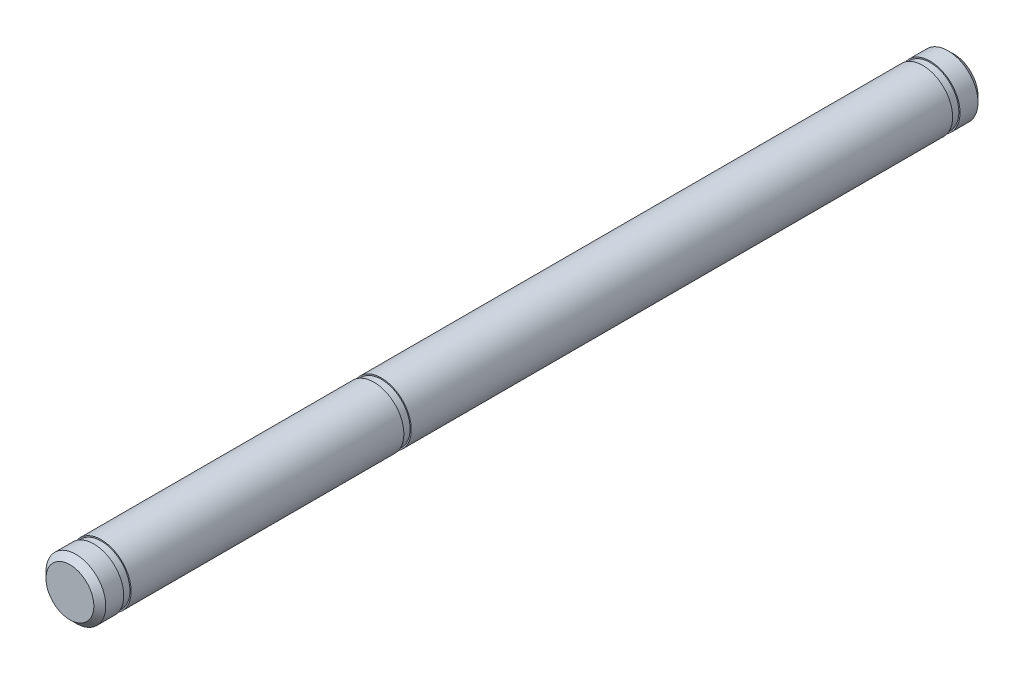
SolidWorks part; units mm, degrees
ref_plane "Front Plane" through (0, 0, 0) normal (0, 0, 1) x (1, 0, 0)
ref_plane "Top Plane" through (0, 0, 0) normal (0, 1, 0) x (1, 0, 0)
ref_plane "Right Plane" through (0, 0, 0) normal (1, 0, 0) x (0, 0, -1)
sketch "Sketch1" plane through (0, 0, 0) normal (0, 0, 1) x (1, 0, 0)
  line L0 (-2.5, 0) -> (2.5, 0) construction
  line L5 (0, 2.5) -> (0, -2.5) construction
  circle A1 centre (0, 0) radius 2.5
  point P7 (-2.5, 0)
  point P8 (2.5, 0)
  point P12 (0, -2.5)
  point P13 (0, 2.5)
  dimension "Diameter" = 5
sketch "Sketch2" plane through (0, 0, 0) normal (1, 0, 0) x (0, 0, -1)
  line L0 (-45, -2.5) -> (-45, 2.5) construction
  line L1 (50, -2.5) -> (-50, -2.5)
  line L2 (50, -2.5) -> (50, 2.5)
  line L3 (50, 2.5) -> (-50, 2.5)
  line L4 (-50, -2.5) -> (-50, 2.5)
  line L5 (50, -2.5) -> (-50, 2.5) construction
  line L6 (50, 2.5) -> (-50, -2.5) construction
  line L7 (45, -2.5) -> (45, 2.5) construction
  line L8 (-50, 2.15) -> (-49.65, 2.5) construction
  point P0 (0, 0)
  point P8 (-50, 2.5)
  point P9 (50, 2.5)
  point P14 (-45, 2.5)
  point P15 (-45, -2.5)
  point P16 (45, 2.5)
  point P17 (45, -2.5)
  point P25 (0, -2.5)
  dimension "Length" = 100
  dimension "D1" = 5
  dimension "D2" = 5
  dimension "Chamfer Typ," = 45
  dimension "D4" = 0.35
sketch "Sketch3" plane through (0, 0, 0) normal (0, 0, 1) x (1, 0, 0)
  circle A0 centre (0, 0) radius 2.5 construction
  circle A1 centre (0, 0) radius 2.5
extrude "Boss-Extrude1" add sketch "Sketch3" along normal up to vertex (50 mm away) and the other way up to vertex (50 mm away) up to point (0, 2.5, 50) other way up to point (0, 2.5, -50)
chamfer "Chamfer1" distance 0.35 angle 45 2 edges at (2.5, 0, -50) (2.5, 0, 50)
sketch "Sketch5" plane through (0, 0, 0) normal (0, 1, 0) x (1, 0, 0)
  line L0 (-2.875, -11.4586) -> (2.875, -11.4586) construction
  line L1 (3.85, 33.6104) -> (-3.85, 33.6104) construction
  line L2 (-3.85, -34.6836) -> (3.85, -34.6836) construction
  line L3 (-2.875, -11.4586) -> (2.875, -11.4586) construction
  line L4 (3.85, 33.6104) -> (-3.85, 33.6104) construction
  line L5 (-3.85, -34.6836) -> (3.85, -34.6836) construction
  line L6 (0, -50) -> (0, 50) construction
  line L7 (2.15, 50) -> (-2.15, 50) construction
  line L8 (-2.15, -50) -> (2.15, -50) construction
  line L9 (2.5, -49.65) -> (2.5, 49.65) construction
  line L10 (2.4, 33.8104) -> (3.4, 33.8104)
  line L11 (2.4, 33.8104) -> (2.4, 34.4304)
  line L12 (2.4, 34.4304) -> (3.4, 34.4304)
  line L13 (3.4, 33.8104) -> (3.4, 34.4304)
  line L14 (0, 36.4304) -> (2.5, 36.4304)
  line L15 (0, 36.4304) -> (0, 50)
  line L16 (0, 50) -> (2.5, 50)
  line L17 (2.5, 36.4304) -> (2.5, 50)
  line L19 (2.4, -34.8836) -> (3.4, -34.8836)
  line L20 (2.4, -34.8836) -> (2.4, -35.5036)
  line L21 (2.4, -35.5036) -> (3.4, -35.5036)
  line L22 (3.4, -34.8836) -> (3.4, -35.5036)
  line L23 (0, -37.5036) -> (2.5, -37.5036)
  line L24 (0, -37.5036) -> (0, -50)
  line L25 (0, -50) -> (2.5, -50)
  line L26 (2.5, -37.5036) -> (2.5, -50)
  line L28 (2.4, -11.4586) -> (3.4, -11.4586)
  line L29 (2.4, -11.4586) -> (2.4, -12.0786)
  line L30 (2.4, -12.0786) -> (3.4, -12.0786)
  line L31 (3.4, -11.4586) -> (3.4, -12.0786)
  point P9 (0, -11.4586)
  point P14 (0, -34.6836)
  point P15 (0, 33.6104)
  point P33 (3.4, -13.1228)
  point P35 (0, 0)
  dimension "D1" = 4.8
  dimension "D2" = 0.62
  dimension "D3" = 1
  dimension "D4" = 0.2
  dimension "D5" = 0.2
  dimension "D6" = 2
  dimension "D7" = 2
ref_plane "Plane1" through (0, 0, 50) normal (-1, 0, 0) x (0, 1, 0)
ref_plane "Plane2" through (0, 0, 50) normal (-1, 0, 0) x (0, 1, 0)
ref_plane "Plane3" through (0, 0, 50) normal (-1, 0, 0) x (0, 1, 0)
ref_plane "Plane4" through (0, 0, 50) normal (-1, 0, 0) x (0, 1, 0)
revolve "Cut-Revolve5" cut sketch "Sketch5" angle 360 about L6
chamfer "Chamfer3" distance 0.5 angle 45 2 edges at (2.5, 0, 37.5036) (2.5, 0, -36.4304)
equation "\"D1@Sketch2\"=\"Diameter@Sketch1\""
equation "\"D2@Sketch2\"=\"Diameter@Sketch1\""
equation "\"D1@Chamfer1\"=\"Diameter@Sketch1\"*.07"
equation "\"D4@Sketch2\"=\"Diameter@Sketch1\"*.07"
equation "\"D2@Chamfer1\"=\"Chamfer Typ,@Sketch2\""
